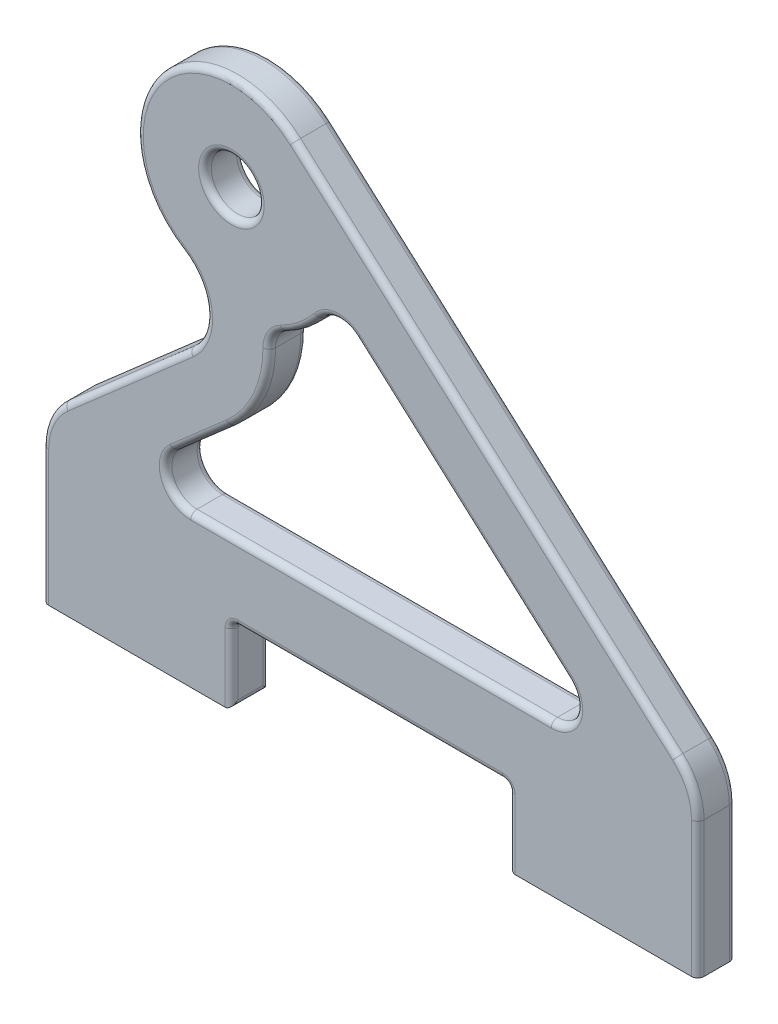
SolidWorks part; units mm, degrees
ref_plane "Front Plane" through (0, 0, 0) normal (0, 0, 1) x (1, 0, 0)
ref_plane "Top Plane" through (0, 0, 0) normal (0, 1, 0) x (1, 0, 0)
ref_plane "Right Plane" through (0, 0, 0) normal (1, 0, 0) x (0, 0, -1)
sketch "Sketch1" plane through (0, 0, 0) normal (0, 0, 1) x (1, 0, 0)
  line L0 (0, 0) -> (15, 0)
  line L1 (15, 0) -> (15, 6)
  line L2 (15, 6) -> (37, 6)
  line L3 (37, 6) -> (37, 0)
  line L4 (37, 0) -> (52, 0)
  line L5 (52, 0) -> (52, 13)
  line L6 (0, 13) -> (11.6339, 23.1789)
  line L7 (52, 13) -> (19.9969, 41.5929)
  line L8 (0, 0) -> (0, 13)
  circle A0 centre (15, 36) radius 2.1
  arc A1 (19.9969, 41.5929) -> (11.087, 29.6017) centre (15, 36) ccw
  arc A2 (11.6339, 23.1789) -> (11.087, 29.6017) centre (9, 26.1893) ccw
  dimension "D5" = 4.2
  dimension "D7" = 15
  dimension "D10" = 8
  dimension "D1" = 15
  dimension "D2" = 6
  dimension "D3" = 22
  dimension "D4" = 15
  dimension "D6" = 36
  dimension "D8" = 15
  dimension "D9" = 13
  dimension "D11" = 9
extrude "Boss-Extrude1" add sketch "Sketch1" along normal blind 3
fillet "Fillet1" radius 5 2 edges at (0, 13, 1.5) (52, 13, 1.5)
sketch "Sketch3" plane through (0, 0, 3) normal (0, 0, 1) x (1, 0, 0)
  line L2 (14.9263, 19.4159) -> (5, 10.731)
  line L3 (14.9263, 19.4159) -> (10.4566, 15.5052)
  line L5 (47, 10.7623) -> (16.6656, 37.8643)
  line L6 (41.7068, 15.4914) -> (24.8601, 30.543)
  line L8 (15, 12) -> (37, 12)
  line L9 (11.7736, 12) -> (40.3743, 12)
  arc A0 (19.0909, 27.9835) -> (21.9771, 30.3149) centre (15, 36) ccw
  arc A2 (19.0909, 27.9835) -> (18, 26.1997) centre (20, 26.202) ccw
  arc A3 (14.9263, 19.4159) -> (13.6957, 33.8672) centre (9, 26.1893) ccw
  arc A4 (14.9263, 19.4159) -> (18, 26.1997) centre (9, 26.1893) ccw
  arc A5 (21.9771, 30.3149) -> (24.8601, 30.543) centre (23.5276, 29.0516) cw
  arc A6 (40.3743, 12) -> (41.7068, 15.4914) centre (40.3743, 14) ccw
  arc A7 (11.7736, 12) -> (10.4566, 15.5052) centre (11.7736, 14) cw
  dimension "D1" = 5
  dimension "D2" = 5
  dimension "D4" = 18
  dimension "D6" = 2
  dimension "D3" = 6
  dimension "D5" = 5
extrude "Cut-Extrude1" cut sketch "Sketch3" against normal blind 10
fillet "Fillet2" radius 0.5 46 edges at (18.2938, 27.2455, 0) (20.6555, 28.9989, 0) (23.3698, 31.0454, 0) (33.2835, 23.0172, 0) (42.2428, 13.2869, 0) (26.0739, 12, 0) (9.9013, 13.2966, 0) (12.6914, 17.4605, 0) (18.2938, 27.2455, 3) (20.6555, 28.9989, 3) (23.3698, 31.0454, 3) (33.2835, 23.0172, 3) (42.2428, 13.2869, 3) (26.0739, 12, 3) (9.9013, 13.2966, 3) (12.6914, 17.4605, 3) (52, 5.3811, 0) (51.5638, 12.8048, 0) (0, 5.3655, 0) (0.4469, 12.7972, 0) (6.6708, 18.8365, 0) (12.9856, 26.5287, 0) (8.98, 40.4732, 0) (52, 5.3811, 3) (51.5638, 12.8048, 3) (0, 5.3655, 3) (0.4469, 12.7972, 3) (6.6708, 18.8365, 3) (12.9856, 26.5287, 3) (8.98, 40.4732, 3) (37, 3, 3) (37, 0, 1.5) (37, 3, 0) (26, 6, 3) (37, 6, 1.5) (26, 6, 0) (15, 0, 1.5) (15, 3, 3) (15, 6, 1.5) (15, 3, 0) (17.1978, 22.4749, 0) (17.1978, 22.4749, 3) (35.1641, 28.0419, 0) (35.1641, 28.0419, 3) (17.1, 36, 0) (17.1, 36, 3)
